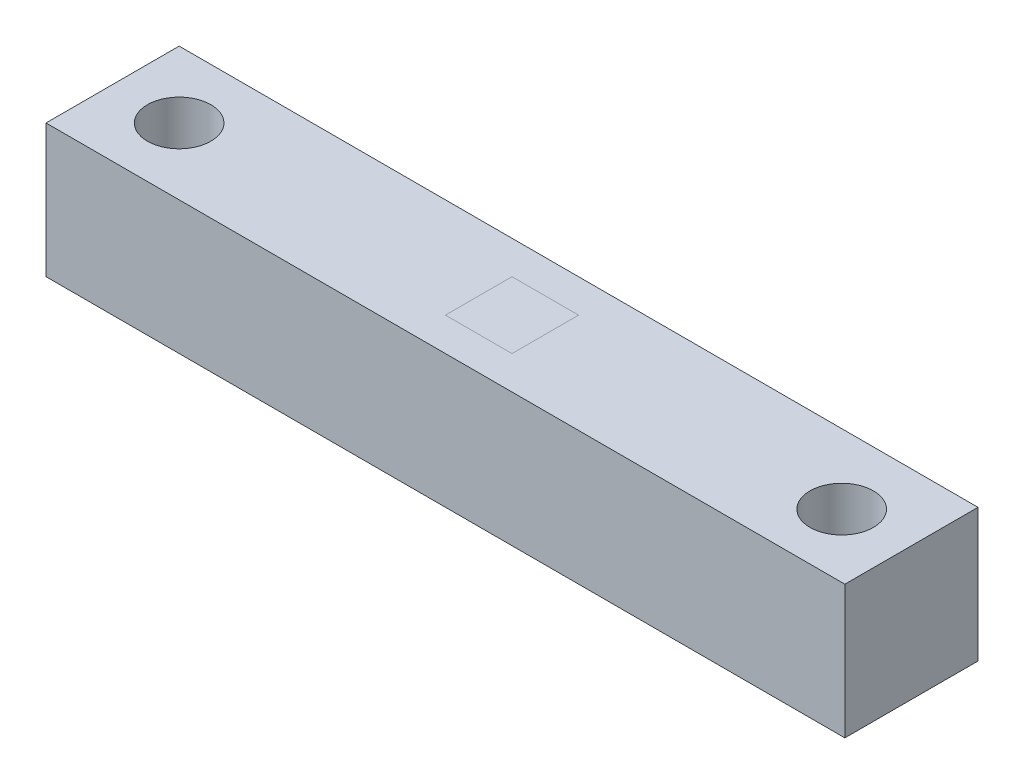
SolidWorks part; units mm, degrees
material "6061 Alloy"
ref_plane "Front Plane" through (0, 0, 0) normal (0, 0, 1) x (1, 0, 0)
ref_plane "Top Plane" through (0, 0, 0) normal (0, 1, 0) x (1, 0, 0)
ref_plane "Right Plane" through (0, 0, 0) normal (1, 0, 0) x (0, 0, -1)
sketch "Sketch1" plane through (0, 0, 0) normal (0, 0, 1) x (1, 0, 0)
  line L1 (120, -20) -> (-120, -20)
  line L2 (120, -20) -> (120, 20)
  line L3 (120, 20) -> (-120, 20)
  line L4 (-120, -20) -> (-120, 20)
  line L5 (120, -20) -> (-120, 20) construction
  line L6 (120, 20) -> (-120, -20) construction
  point P0 (0, 0)
  dimension "D1" = 240
  dimension "D2" = 40
extrude "Boss-Extrude1" add sketch "Sketch1" along normal blind 40
sketch "Sketch3" plane through (0, 20, 0) normal (0, 1, 0) x (1, 0, 0)
  line L0 (120, 0) -> (-120, 0) construction
  line L1 (-120, -40) -> (-120, 0) construction
  line L2 (120, -40) -> (-120, -40) construction
  circle A0 centre (-100, -20) radius 9.525
  circle A1 centre (100, -20.95) radius 9.525
  dimension "D4" = 19.05
  dimension "D1" = 20
  dimension "D2" = 200
  dimension "D3" = 20
  dimension "D5" = 19.05
extrude "Cut-Extrude4" cut sketch "Sketch3" against normal through all
sketch "Sketch4" plane through (0, 20, 0) normal (0, 1, 0) x (1, 0, 0)
  line L0 (-120, -40) -> (-120, 0) construction
  line L1 (10, -30) -> (-10, -30)
  line L2 (10, -30) -> (10, -10)
  line L3 (10, -10) -> (-10, -10)
  line L4 (-10, -30) -> (-10, -10)
  line L5 (10, -30) -> (-10, -10) construction
  line L6 (10, -10) -> (-10, -30) construction
  line L8 (120, -40) -> (-120, -40) construction
  point P0 (0, -20)
  point P7 (0, 0)
  dimension "D1" = 20
  dimension "D2" = 20
  dimension "D3" = 110
  dimension "D4" = 10
split line "Split Line1"
